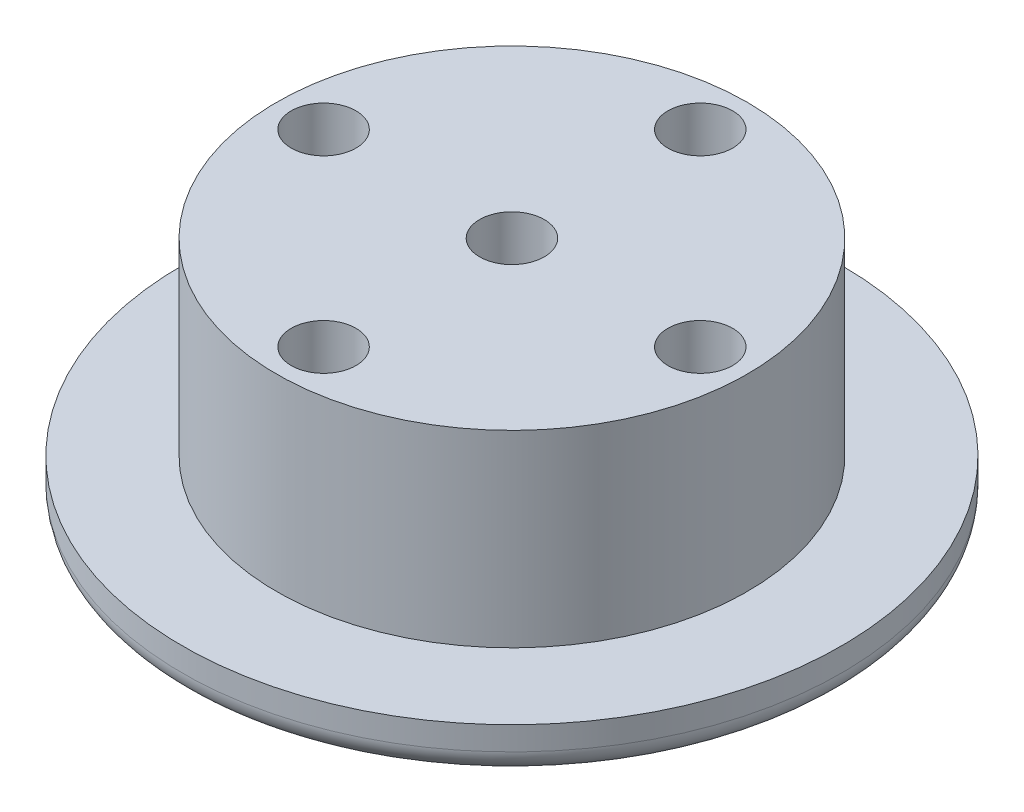
SolidWorks part; units mm, degrees
ref_plane "Front Plane" through (0, 0, 0) normal (0, 0, 1) x (1, 0, 0)
ref_plane "Top Plane" through (0, 0, 0) normal (0, 1, 0) x (1, 0, 0)
ref_plane "Right Plane" through (0, 0, 0) normal (1, 0, 0) x (0, 0, -1)
sketch "Sketch1" plane through (0, 0, 0) normal (0, 0, 1) x (1, 0, 0)
  line L0 (0, 0) -> (0, 15.875)
  line L1 (0, 15.875) -> (15.875, 15.875)
  line L2 (15.875, 15.875) -> (15.875, 3.175)
  line L3 (15.875, 3.175) -> (22.225, 3.175)
  line L4 (22.225, 3.175) -> (22.225, 1.5875)
  line L5 (20.6375, 0) -> (0, 0)
  arc A0 (20.6375, 0) -> (22.225, 1.5875) centre (20.6375, 1.5875) ccw
  dimension "D5" = 1.5875
  dimension "D1" = 15.875
  dimension "D2" = 3.175
  dimension "D3" = 12.7
  dimension "D4" = 6.35
revolve "Revolve2" add sketch "Sketch1" angle 360 about L0
sketch "Sketch3" plane through (0, 15.875, 0) normal (0, 1, 0) x (1, 0, 0)
  circle A0 centre (0, 0) radius 2.1828
  circle A1 centre (12.7, 0) radius 2.1828
  circle A2 centre (-12.7, 0) radius 2.1828
  circle A3 centre (0, -12.7) radius 2.1828
  circle A4 centre (0, 12.7) radius 2.1828
  dimension "D1" = 4.3656
  dimension "D3" = 4.3656
  dimension "D5" = 4.3656
  dimension "D7" = 4.3656
  dimension "D9" = 4.3656
  dimension "D2" = 12.7
  dimension "D4" = 12.7
  dimension "D6" = 12.7
  dimension "D8" = 12.7
extrude "Cut-Extrude1" cut sketch "Sketch3" against normal through all both and the other way through all
